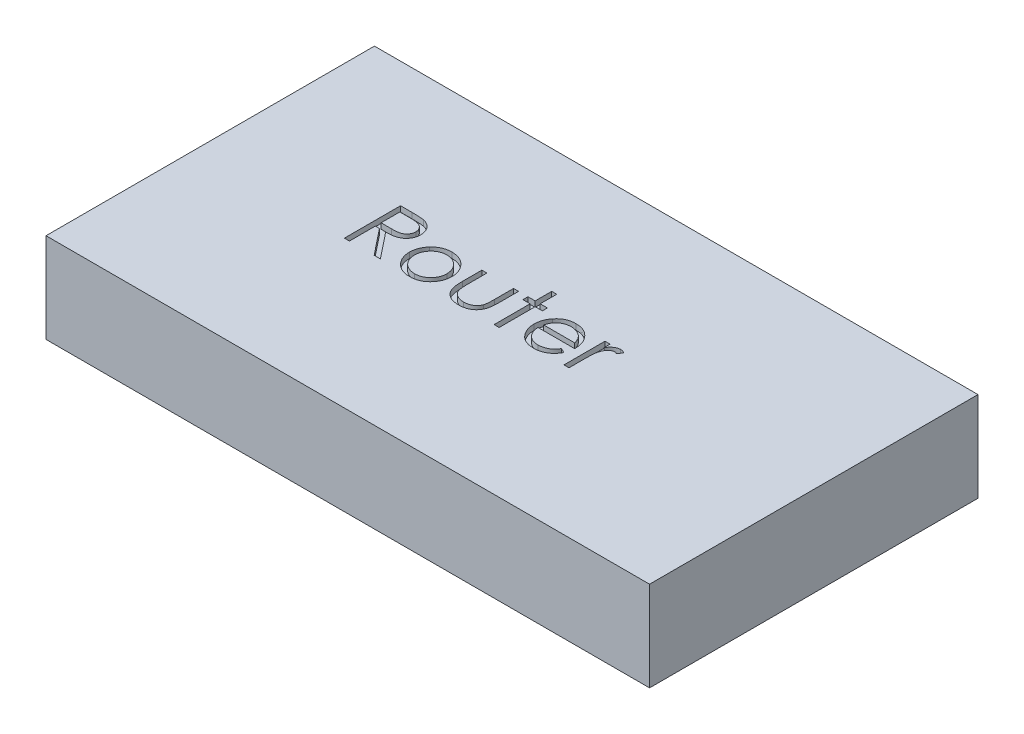
SolidWorks part; units mm, degrees
ref_plane "Front Plane" through (0, 0, 0) normal (0, 0, 1) x (1, 0, 0)
ref_plane "Top Plane" through (0, 0, 0) normal (0, 1, 0) x (1, 0, 0)
ref_plane "Right Plane" through (0, 0, 0) normal (1, 0, 0) x (0, 0, -1)
sketch "Sketch1" plane through (0, 0, 0) normal (0, 1, 0) x (1, 0, 0)
  line L1 (-215, 117) -> (0, 117)
  line L2 (-215, 117) -> (-215, 0)
  line L3 (-215, 0) -> (0, 0)
  line L4 (0, 117) -> (0, 0)
  dimension "D1" = 117
  dimension "D2" = 215
extrude "Boss-Extrude1" add sketch "Sketch1" along normal blind 32
sketch "Sketch3" plane through (0, 32, 0) normal (0, 1, 0) x (1, 0, 0)
  line L0 (-196.3898, 52.3997) -> (-43.5093, 52.3997) construction
  text T0 "Router" font "Century Gothic" height 20
extrude "Cut-Extrude2" cut sketch "Sketch3" against normal blind 2
